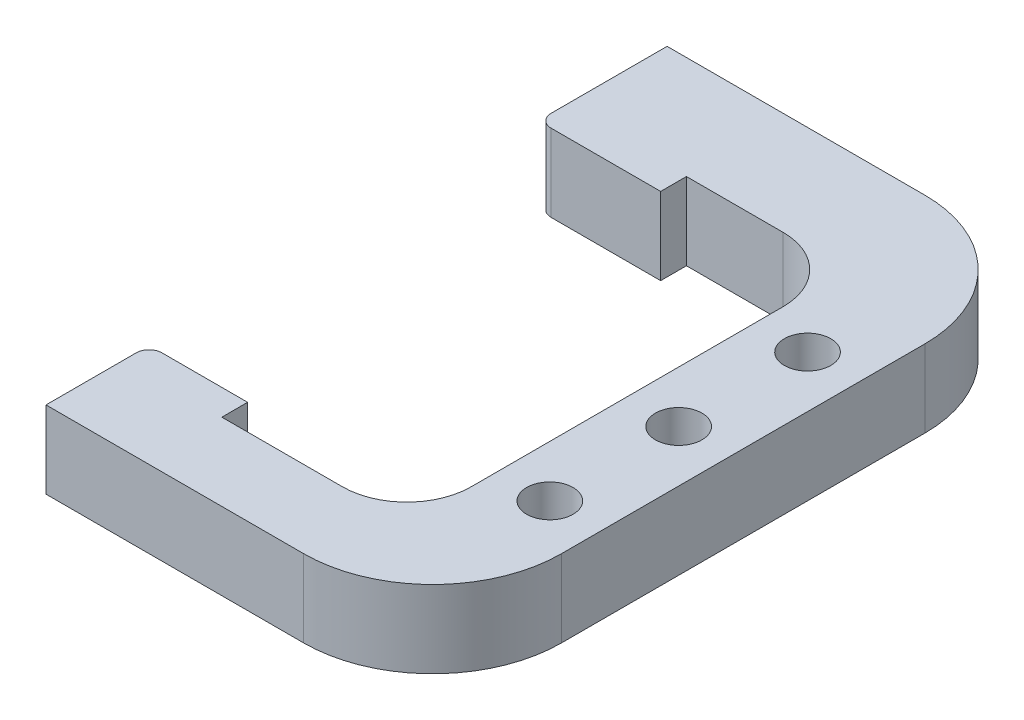
SolidWorks part; units mm, degrees
ref_plane "Alzado" through (0, 0, 0) normal (0, 0, 1) x (1, 0, 0)
ref_plane "Planta" through (0, 0, 0) normal (0, 1, 0) x (1, 0, 0)
ref_plane "Vista lateral" through (0, 0, 0) normal (1, 0, 0) x (0, 0, -1)
sketch "Croquis1" plane through (0, 0, 0) normal (0, 1, 0) x (1, 0, 0)
  line L1 (0, -36.6) -> (0, -28.6)
  line L2 (0, 1.6) -> (0, 11.6)
  line L3 (0, 11.6) -> (30, 11.6)
  line L4 (30, 11.6) -> (30, -36.6)
  line L5 (30, -36.6) -> (0, -36.6)
  line L6 (22, -28.6) -> (22, 1.6)
  line L9 (22, 1.6) -> (22, 3.6)
  line L10 (22, 3.6) -> (9.5009, 3.6)
  line L11 (9.5009, 3.6) -> (9.5009, 1.6)
  line L12 (0, 1.6) -> (9.5009, 1.6)
  line L13 (0, -28.6) -> (7.6467, -28.6)
  line L14 (7.6467, -28.6) -> (7.6467, -30.6)
  line L15 (7.6467, -30.6) -> (22, -30.6)
  line L16 (22, -30.6) -> (22, -28.6)
  point P4 (0, 0)
  dimension "D1" = 30.2
  dimension "D2" = 2
  dimension "D3" = 30
  dimension "D4" = 8
  dimension "D5" = 10
  dimension "D6" = 22
  dimension "D7" = 2
extrude "Saliente-Extruir1" add sketch "Croquis1" along normal blind 6
fillet "Redondeo1" radius 10 2 edges at (30, 3, -11.6) (30, 3, 36.6)
fillet "Redondeo2" radius 5 2 edges at (22, 3, -3.6) (22, 3, 30.6)
fillet "Redondeo3" radius 1 2 edges at (0, 3, -1.6) (0, 3, 28.6)
sketch "Croquis2" plane through (0, 6, 0) normal (0, 1, 0) x (1, 0, 0)
  line L0 (22, -13.5) -> (30, -13.5) construction
  line L1 (22, -1.4) -> (22, -25.6) construction
  line L2 (30, -26.6) -> (30, 1.6) construction
  circle A0 centre (26, -13.5) radius 1.8033
extrude "Cortar-Extruir1" cut sketch "Croquis2" against normal blind 6
pattern_linear "MatrizL1" count 2 spacing 10 along (0, 0, 1) of "Cortar-Extruir1"
pattern_linear "MatrizL2" count 2 spacing 10 along (0, 0, -1) of "Cortar-Extruir1"
